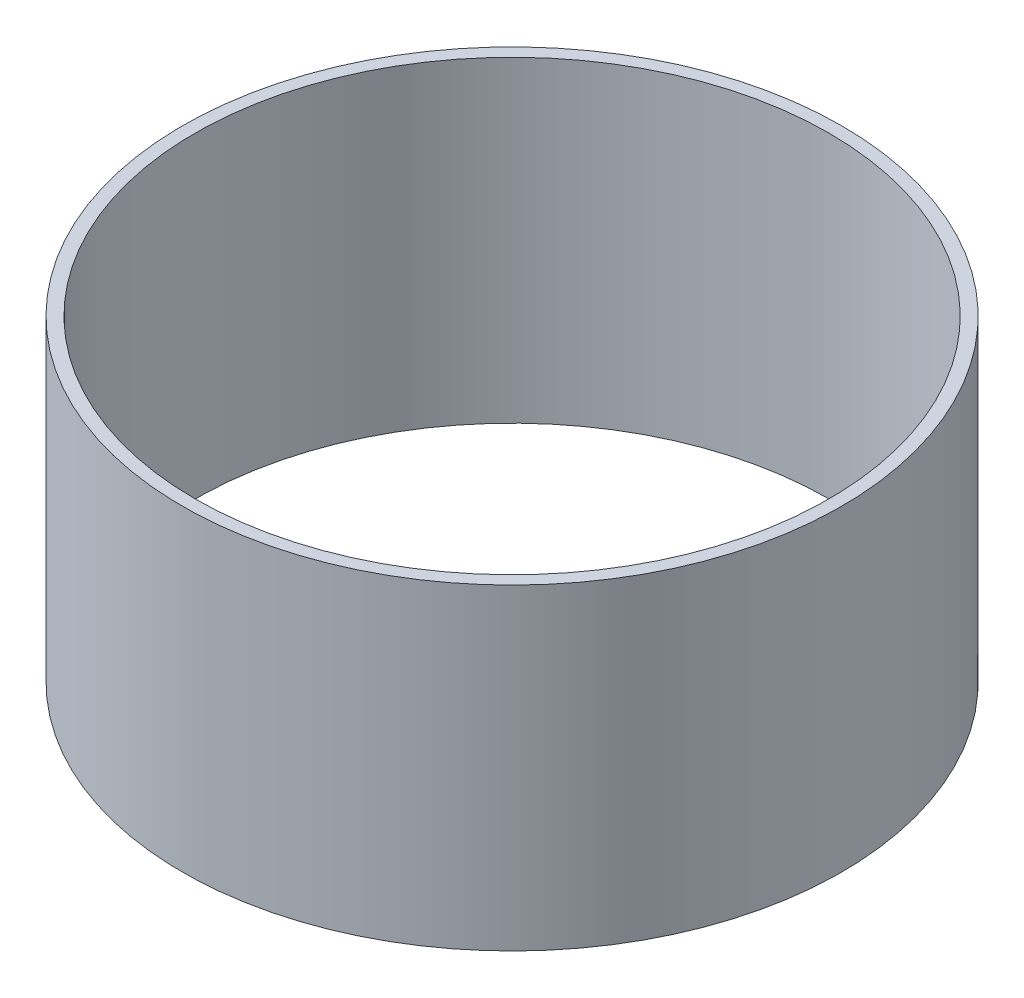
SolidWorks part; units mm, degrees
material "S-Glass Fiber"
ref_plane "Front Plane" through (0, 0, 0) normal (0, 0, 1) x (1, 0, 0)
ref_plane "Top Plane" through (0, 0, 0) normal (0, 1, 0) x (1, 0, 0)
ref_plane "Right Plane" through (0, 0, 0) normal (1, 0, 0) x (0, 0, -1)
sketch "Sketch1" plane through (0, 0, 0) normal (0, 1, 0) x (1, 0, 0)
  circle A0 centre (0, 0) radius 38.1
  circle A1 centre (0, 0) radius 39.624
  dimension "D1" = 76.2
  dimension "D2" = 79.248
extrude "Boss-Extrude1" add sketch "Sketch1" along normal blind 38.1
